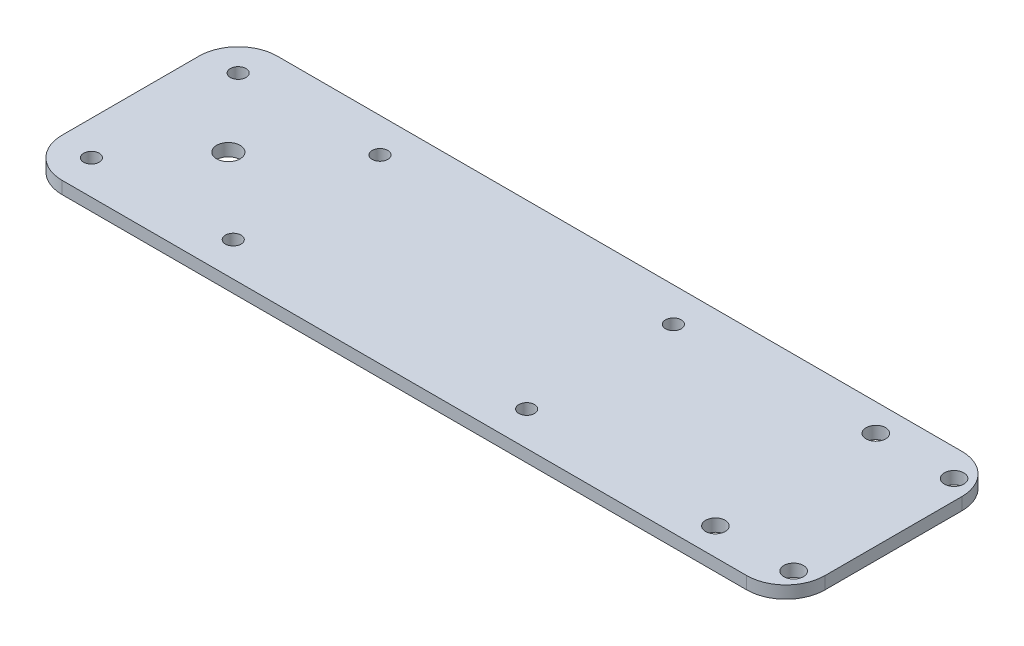
SolidWorks part; units mm, degrees
ref_plane "Front Plane" through (0, 0, 0) normal (0, 0, 1) x (1, 0, 0)
ref_plane "Top Plane" through (0, 0, 0) normal (0, 1, 0) x (1, 0, 0)
ref_plane "Right Plane" through (0, 0, 0) normal (1, 0, 0) x (0, 0, -1)
sketch "Sketch1" plane through (0, 0, 0) normal (0, 1, 0) x (1, 0, 0)
  line L0 (-25, 0) -> (0, 0) construction
  line L1 (-25, 27.5) -> (170, 27.5)
  line L2 (-25, 27.5) -> (-25, -27.5)
  line L3 (-25, -27.5) -> (170, -27.5)
  line L4 (170, 27.5) -> (170, -27.5)
  point P7 (150, 0)
  dimension "D1" = 55
  dimension "D2" = 150
  dimension "D3" = 20
  dimension "D4" = 25
extrude "Boss-Extrude1" add sketch "Sketch1" along normal blind 3.175
fillet "Fillet1" radius 10 4 edges at (-25, 1.5875, 27.5) (-25, 1.5875, -27.5) (170, 1.5875, -27.5) (170, 1.5875, 27.5)
hole_wizard "Ø6.0mm Dowel Hole1" positions "Sketch3" profile "Sketch4" hole size "Ø6.0" standard "DIN" end condition up to next
sketch "Sketch3" plane through (0, 3.175, 0) normal (0, 1, 0) x (1, 0, 0)
  point P0 (0, 0)
sketch "Sketch4" plane through (0, 3.175, 0) normal (1, 0, 0) x (0, 0, 1)
  line L0 (0, 0) -> (0, 3.175)
  line L1 (0, 3.175) -> (3, 3.175)
  line L2 (3, 3.175) -> (3, 0)
  line L5 (3, 0) -> (0, 0)
  line L11 (0, -6.35) -> (0, 107.95) construction
  dimension "Thru Hole Dia." = 6
  dimension "Thru Hole Depth" = 3.175
hole_wizard "Ø4.0mm Dowel Hole1" positions "Sketch5" profile "Sketch6" hole size "Ø4.0" standard "DIN" end condition up to next
sketch "Sketch5" plane through (0, 3.175, 0) normal (0, 1, 0) x (1, 0, 0)
  line L0 (-25, 17.5) -> (-25, -17.5) construction
  line L1 (-15, -27.5) -> (160, -27.5) construction
  line L3 (-25, 0) -> (170, 0) construction
  line L4 (170, -17.5) -> (170, 17.5) construction
  circle A0 centre (0, 0) radius 3 construction
  point P0 (-16.25, -18.75)
  point P2 (20, -18.75)
  point P15 (95, -18.75)
  point P26 (95, 18.75)
  point P27 (20, 18.75)
  point P28 (-16.25, 18.75)
  dimension "D3" = 20
  dimension "D1" = 8.75
  dimension "D2" = 8.75
  dimension "D5" = 75
  dimension "D4" = 2
sketch "Sketch6" plane through (-16.25, 3.175, 18.75) normal (1, 0, 0) x (0, 0, 1)
  line L0 (0, 0) -> (0, 3.175)
  line L1 (0, 3.175) -> (2, 3.175)
  line L2 (2, 3.175) -> (2, 0)
  line L5 (2, 0) -> (0, 0)
  line L11 (0, -6.35) -> (0, 107.95) construction
  dimension "Thru Hole Dia." = 4
  dimension "Thru Hole Depth" = 3.175
hole_wizard "Ø5.0mm Dowel Hole1" positions "Sketch7" profile "Sketch8" hole size "Ø5.0" standard "DIN" end condition through all
sketch "Sketch7" plane through (0, 3.175, 0) normal (0, 1, 0) x (1, 0, 0)
  line L0 (155, 27.5) -> (155, -27.5) construction
  line L1 (160, 27.5) -> (-15, 27.5) construction
  line L2 (-15, -27.5) -> (160, -27.5) construction
  line L4 (170, -17.5) -> (170, 17.5) construction
  line L5 (170, 0) -> (-25, 0) construction
  line L6 (-25, 17.5) -> (-25, -17.5) construction
  point P0 (165, 20.5)
  point P20 (145, 20.5)
  point P21 (165, -20.5)
  point P22 (145, -20.5)
  dimension "D1" = 15
  dimension "D2" = 5
  dimension "D3" = 7
sketch "Sketch8" plane through (165, 3.175, -20.5) normal (1, 0, 0) x (0, 0, 1)
  line L0 (0, 0) -> (0, 3.175)
  line L1 (0, 3.175) -> (2.5, 3.175)
  line L2 (2.5, 3.175) -> (2.5, 0)
  line L5 (2.5, 0) -> (0, 0)
  line L11 (0, -6.35) -> (0, 107.95) construction
  dimension "Thru Hole Dia." = 5
  dimension "Thru Hole Depth" = 3.175
equation "\"Pivot to Pivot Distance\"= 150mm"
equation "\"D2@Sketch1\"=\"Pivot to Pivot Distance\""
equation "\"Plate Thickness\"= 0.125in"
equation "\"D1@Boss-Extrude1\"=\"Plate Thickness\""
